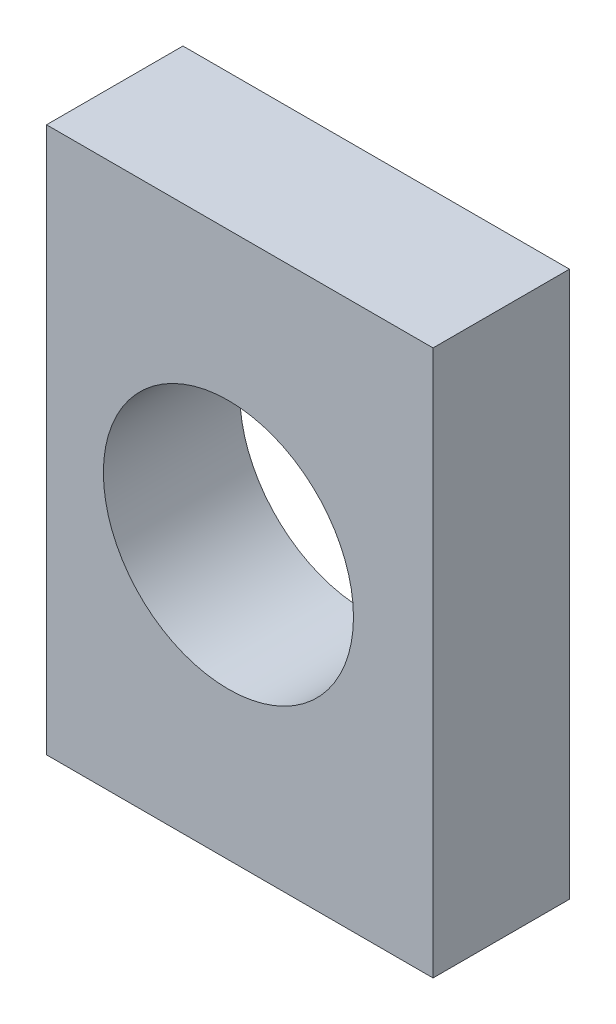
SolidWorks part; units mm, degrees
ref_plane "Front Plane" through (0, 0, 0) normal (0, 0, 1) x (1, 0, 0)
ref_plane "Top Plane" through (0, 0, 0) normal (0, 1, 0) x (1, 0, 0)
ref_plane "Right Plane" through (0, 0, 0) normal (1, 0, 0) x (0, 0, -1)
sketch "M5 attachment profile" plane through (0, 0, 0) normal (0, 0, 1) x (1, 0, 0)
  line L0 (94.5, -6) -> (103, -6)
  line L1 (103, -6) -> (103, 6)
  line L2 (103, 6) -> (94.5, 6)
  line L3 (94.5, 6) -> (94.5, -6)
  circle A0 centre (98.5, 0) radius 2.75
extrude "M5 attachment" add sketch "M5 attachment profile" along normal blind 3
